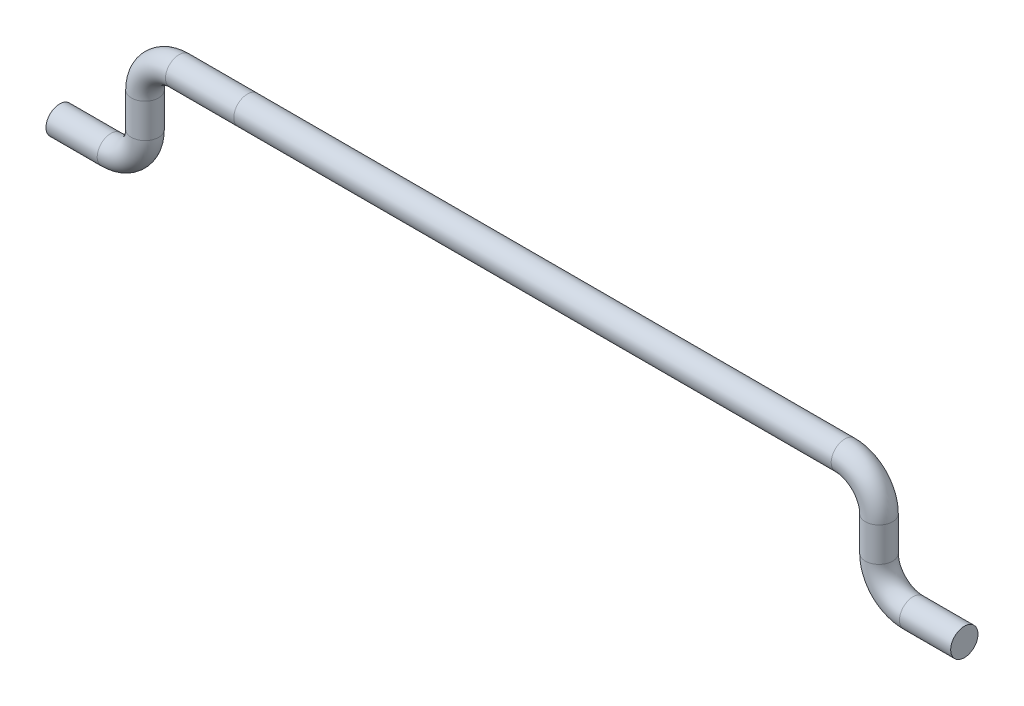
SolidWorks part; units mm, degrees
ref_plane "Front Plane" through (0, 0, 0) normal (0, 0, 1) x (1, 0, 0)
ref_plane "Top Plane" through (0, 0, 0) normal (0, 1, 0) x (1, 0, 0)
ref_plane "Right Plane" through (0, 0, 0) normal (1, 0, 0) x (0, 0, -1)
sketch "Sketch12" plane through (0, 0, 0) normal (0, 0, 1) x (1, 0, 0)
  line L0 (6.129, 0) -> (-38.321, 0)
  line L1 (8.669, -2.54) -> (8.669, -5.08)
  line L2 (11.209, -7.62) -> (15.019, -7.62)
  line L3 (-38.321, 0) -> (-43.401, 0)
  line L4 (-45.941, -2.54) -> (-45.941, -5.08)
  line L5 (-48.481, -7.62) -> (-52.291, -7.62)
  arc A0 (8.669, -2.54) -> (6.129, 0) centre (6.129, -2.54) ccw
  arc A1 (11.209, -7.62) -> (8.669, -5.08) centre (11.209, -5.08) cw
  arc A2 (-45.941, -5.08) -> (-48.481, -7.62) centre (-48.481, -5.08) cw
  arc A3 (-45.941, -2.54) -> (-43.401, 0) centre (-43.401, -2.54) cw
  point P9 (8.669, 0)
  point P12 (8.669, -7.62)
  point P14 (-45.941, 0)
  point P17 (-45.941, -7.62)
  point P20 (-45.941, 0)
  dimension "D5" = 2.54
  dimension "D6" = 2.54
  dimension "D7" = 7.62
  dimension "D8" = 2.54
  dimension "D9" = 2.54
  dimension "D1" = 54.61
  dimension "D2" = 7.62
  dimension "D3" = 6.35
  dimension "D4" = 6.35
sweep "Sweep2" add path "Sketch12" circular profile diameter 2.032 parameters "D3"=2.032
